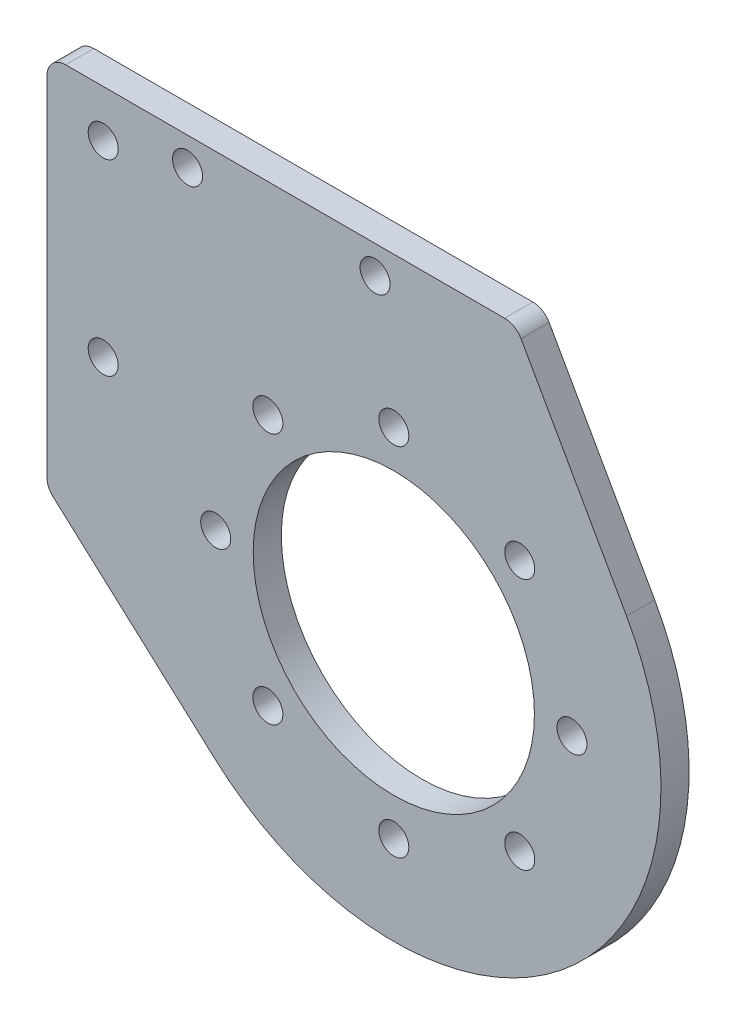
SolidWorks part; units mm, degrees
material "Thornel Mat VMA"
ref_plane "前视基准面" through (0, 0, 0) normal (0, 0, 1) x (1, 0, 0)
ref_plane "上视基准面" through (0, 0, 0) normal (0, 1, 0) x (1, 0, 0)
ref_plane "右视基准面" through (0, 0, 0) normal (1, 0, 0) x (0, 0, -1)
sketch "草图2" plane through (0, 0, 0) normal (0, 0, 1) x (1, 0, 0)
  circle A0 centre (0, 0) radius 15
  circle A1 centre (0, 0) radius 19 construction
  circle A2 centre (0, 0) radius 28.5
  circle A3 centre (0, 19) radius 1.6
  circle A4 centre (13.435, 13.435) radius 1.6
  circle A5 centre (19, 0) radius 1.6
  circle A6 centre (13.435, -13.435) radius 1.6
  circle A7 centre (0, -19) radius 1.6
  circle A8 centre (-13.435, -13.435) radius 1.6
  circle A9 centre (-19, 0) radius 1.6
  circle A10 centre (-13.435, 13.435) radius 1.6
  point P7 (-21.0962, -0.9609)
  point P8 (0, 0)
  point P16 (0, 0)
  dimension "D1" = 38
  dimension "D2" = 3.2
  dimension "D3" = 30
  dimension "D5" = 57
  dimension "D4" = 8
extrude "凸台-拉伸1" add sketch "草图2" along normal blind 3
sketch "草图4" plane through (0, 0, 3) normal (0, 0, 1) x (1, 0, 0)
  line L0 (-36.3399, -5.5957) -> (-19.0934, -21.1587)
  line L1 (-37, -4.1109) -> (-37, 33)
  line L2 (-35, 35) -> (11.8309, 35)
  line L3 (13.5736, 33.9813) -> (24.8339, 13.9831)
  circle A0 centre (-31, 30) radius 1.6
  circle A1 centre (-31, 10) radius 1.6
  circle A2 centre (0, 0) radius 28.5 construction
  circle A3 centre (-22, 32) radius 1.6
  circle A4 centre (-2, 32) radius 1.6
  arc A5 (24.8339, 13.9831) -> (-19.0934, -21.1587) centre (0, 0) ccw
  arc A6 (11.8309, 35) -> (13.5736, 33.9813) centre (11.8309, 33) cw
  arc A7 (-37, 33) -> (-35, 35) centre (-35, 33) cw
  arc A8 (-36.3399, -5.5957) -> (-37, -4.1109) centre (-35, -4.1109) cw
  point P15 (0, 0)
  point P16 (12.9111, 35)
  point P20 (13, 35)
  point P23 (-37, 35)
  point P26 (-37, -5)
  dimension "D1" = 3.2
  dimension "D7" = 3.2
  dimension "D13" = 2
  dimension "D2" = 20
  dimension "D3" = 30
  dimension "D4" = 5
  dimension "D5" = 6
  dimension "D6" = 31
  dimension "D8" = 3
  dimension "D9" = 20
  dimension "D10" = 15
  dimension "D11" = 40
  dimension "D12" = 50
extrude "凸台-拉伸2" add sketch "草图4" against normal up to surface (3 mm away) up to face at (28.5, 0, 0)
